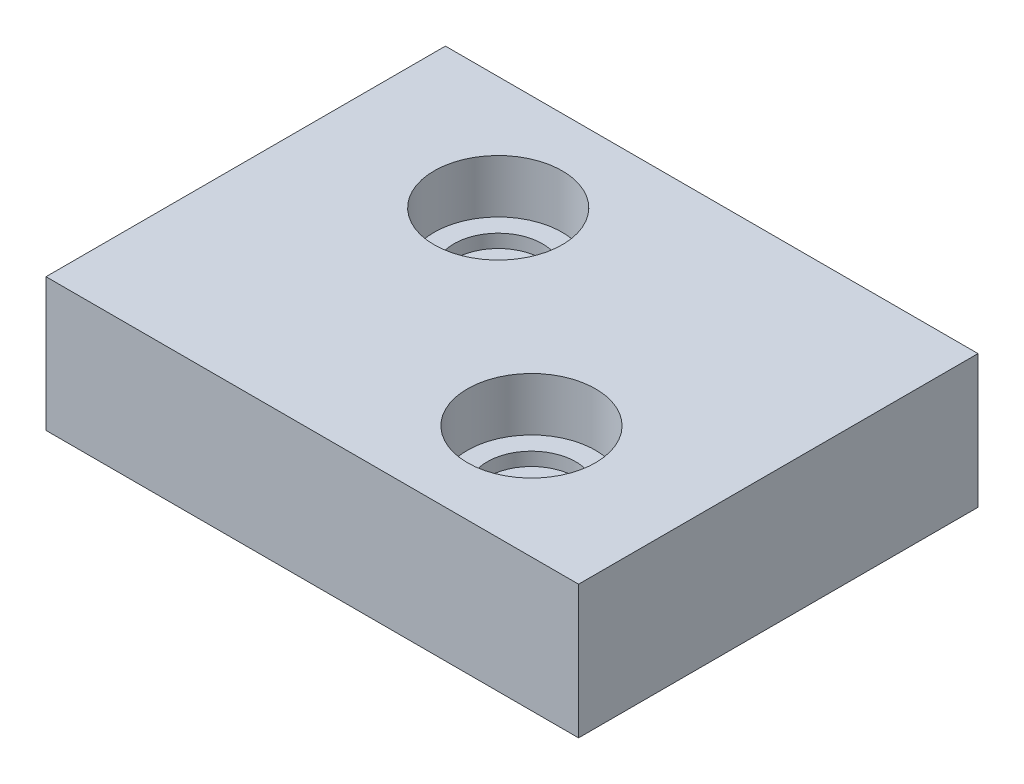
SolidWorks part; units mm, degrees
ref_plane "Front Plane" through (0, 0, 0) normal (0, 0, 1) x (1, 0, 0)
ref_plane "Top Plane" through (0, 0, 0) normal (0, 1, 0) x (1, 0, 0)
ref_plane "Right Plane" through (0, 0, 0) normal (1, 0, 0) x (0, 0, -1)
sketch "Sketch2" plane through (0, 0, 0) normal (0, 1, 0) x (1, 0, 0)
  line L1 (-20, -15) -> (20, -15)
  line L2 (-20, -15) -> (-20, 15)
  line L3 (-20, 15) -> (20, 15)
  line L4 (20, -15) -> (20, 15)
  line L5 (-20, -15) -> (20, 15) construction
  line L6 (-20, 15) -> (20, -15) construction
  point P0 (0, 0)
  dimension "D1" = 40
  dimension "D2" = 30
extrude "Boss-Extrude1" add sketch "Sketch2" along normal blind 10
sketch "Sketch3" plane through (0, 0, 0) normal (0, -1, 0) x (-1, 0, 0)
  line L0 (20, -15) -> (-20, 15) construction
  line L1 (-20, -15) -> (20, 15) construction
  line L2 (0, -15) -> (0, 15) construction
  line L3 (20, -15) -> (-20, -15) construction
  line L4 (-20, 15) -> (20, 15) construction
  line L5 (20, 0) -> (-20, 0) construction
  line L6 (20, 15) -> (20, -15) construction
  line L7 (-20, -15) -> (-20, 15) construction
  circle A0 centre (-13.3333, -10) radius 1.55
  circle A1 centre (13.3333, -10) radius 1.55
  circle A2 centre (-13.3333, 10) radius 1.55
  circle A3 centre (13.3333, 10) radius 1.55
  dimension "D1" = 3.1
  dimension "D2" = 5
extrude "Cut-Extrude1" cut sketch "Sketch3" against normal blind 4
sketch "Sketch4" plane through (0, 10, 0) normal (0, 1, 0) x (1, 0, 0)
  line L0 (20, -15) -> (20, 15) construction
  line L1 (-20, -15) -> (20, -15) construction
  line L2 (-20, 15) -> (-20, -15) construction
  line L4 (7.9286, -6.465) -> (7.9286, 6.4636) construction
  circle A0 centre (7.9286, -6.465) radius 4.8125
  circle A1 centre (-7.5, 6.4636) radius 4.8125
  point P11 (0, 0)
  point P12 (0, 0)
  dimension "D1" = 9.625
  dimension "D6" = 9.625
  dimension "D2" = 12.0714
  dimension "D3" = 8.535
  dimension "D4" = 12.5
  dimension "D5" = 12.9286
extrude "Cut-Extrude2" cut sketch "Sketch4" against normal blind 4
sketch "Sketch7" plane through (0, 6, 0) normal (0, 1, 0) x (1, 0, 0)
  circle A0 centre (7.9286, -6.465) radius 3.325
  circle A1 centre (-7.5, 6.4636) radius 3.325
  dimension "D1" = 6.65
  dimension "D2" = 6.65
extrude "Cut-Extrude3" cut sketch "Sketch7" against normal blind 1
